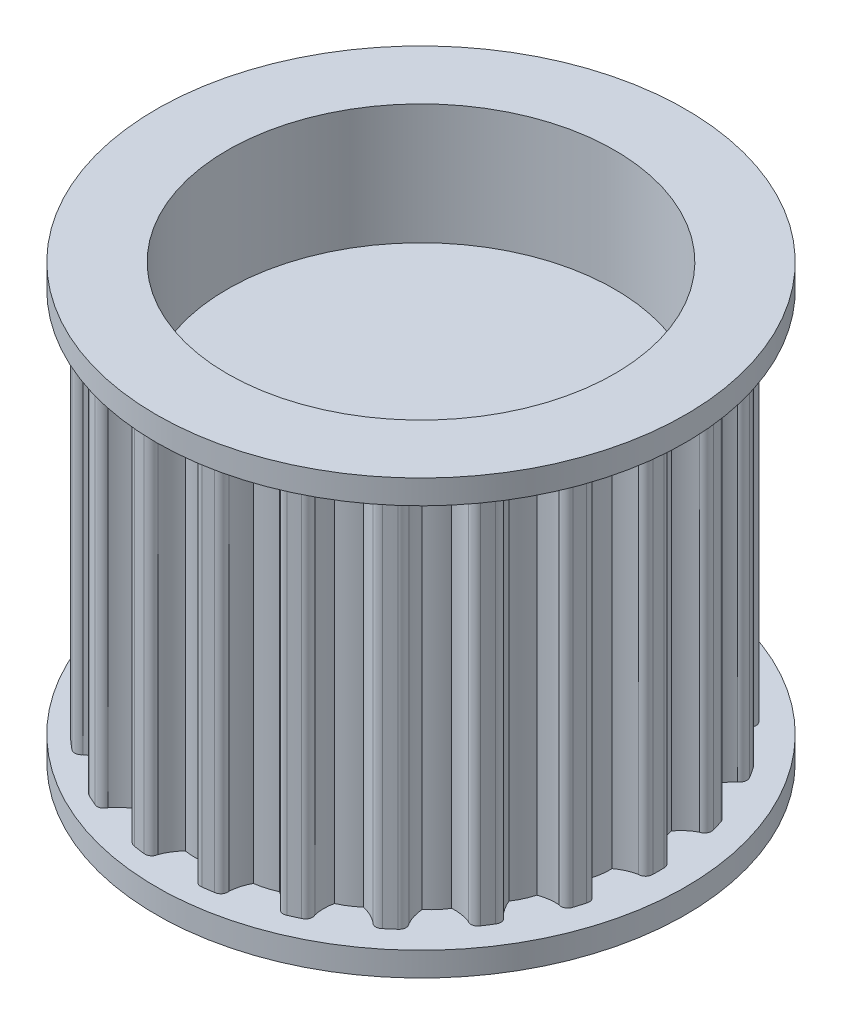
SolidWorks part; units mm, degrees
ref_plane "Front Plane" through (0, 0, 0) normal (0, 0, 1) x (1, 0, 0)
ref_plane "Top Plane" through (0, 0, 0) normal (0, 1, 0) x (1, 0, 0)
ref_plane "Right Plane" through (0, 0, 0) normal (1, 0, 0) x (0, 0, -1)
sketch "Sketch1" plane through (0, 0, 0) normal (0, 1, 0) x (1, 0, 0)
  arc A0 (-3.8587, 9.1521) -> (-4.2814, 9.2843) centre (-4.1212, 9.0547) ccw
  arc A1 (-4.2551, 9.3025) -> (-4.2814, 9.2843) centre (-2.0409, 6.0726) ccw
  arc A2 (-4.2551, 9.3025) -> (-4.6705, 9.1128) centre (-0.2578, 0) ccw
  arc A3 (-4.6394, 9.1208) -> (-4.6705, 9.1128) centre (-3.6795, 5.3243) ccw
  arc A4 (-4.6394, 9.1208) -> (-4.8163, 8.7148) centre (-4.5708, 8.8494) ccw
  arc A5 (-4.7705, 8.2917) -> (-4.8163, 8.7148) centre (-6.7455, 8.2917) ccw
  arc A6 (-4.8114, 7.8919) -> (-4.7705, 8.2917) centre (-6.7455, 8.2917) ccw
  arc A7 (-4.8114, 7.8919) -> (-5.5448, 7.4205) centre (-3.6795, 5.3243) ccw
  arc A8 (-6.2913, 7.7669) -> (-5.5448, 7.4205) centre (-5.1051, 9.3459) ccw
  arc A9 (-6.2913, 7.7669) -> (-6.7341, 7.7746) centre (-6.5157, 7.5994) ccw
  arc A10 (-6.714, 7.7995) -> (-6.7341, 7.7746) centre (-3.6795, 5.3243) ccw
  arc A11 (-6.714, 7.7995) -> (-7.0591, 7.5005) centre (-0.2578, 0) ccw
  arc A12 (-7.0316, 7.5169) -> (-7.0591, 7.5005) centre (-5.0409, 4.1446) ccw
  arc A13 (-7.0316, 7.5169) -> (-7.0869, 7.0775) centre (-6.8893, 7.2758) ccw
  arc A14 (-6.8503, 6.2893) -> (-7.0869, 7.0775) centre (-8.8187, 6.128) ccw
  arc A15 (-6.8503, 6.2893) -> (-7.4213, 5.6304) centre (-5.0409, 4.1446) ccw
  arc A16 (-8.2351, 5.7524) -> (-7.4213, 5.6304) centre (-7.5418, 7.6017) ccw
  arc A17 (-8.2351, 5.7524) -> (-8.6622, 5.6351) centre (-8.4032, 5.5285) ccw
  arc A18 (-8.6499, 5.6647) -> (-8.6622, 5.6351) centre (-5.0409, 4.1446) ccw
  arc A19 (-8.6499, 5.6647) -> (-8.8968, 5.2805) centre (-0.2578, 0) ccw
  arc A20 (-8.875, 5.304) -> (-8.8968, 5.2805) centre (-6.0148, 2.6292) ccw
  arc A21 (-8.875, 5.304) -> (-8.8043, 4.8668) centre (-8.6705, 5.1127) ccw
  arc A22 (-8.3552, 4.1772) -> (-8.8043, 4.8668) centre (-10.1984, 3.4679) ccw
  arc A23 (-8.3552, 4.1772) -> (-8.7174, 3.3841) centre (-6.0148, 2.6292) ccw
  arc A24 (-9.5326, 3.2719) -> (-8.7174, 3.3841) centre (-9.3883, 5.2417) ccw
  arc A25 (-9.5326, 3.2719) -> (-9.9093, 3.039) centre (-9.6309, 3.0097) ccw
  arc A26 (-9.9058, 3.0709) -> (-9.9093, 3.039) centre (-6.0148, 2.6292) ccw
  arc A27 (-9.9058, 3.0709) -> (-10.0345, 2.6327) centre (-0.2578, 0) ccw
  arc A28 (-10.0202, 2.6614) -> (-10.0345, 2.6327) centre (-6.5224, 0.9007) ccw
  arc A29 (-10.0202, 2.6614) -> (-9.8292, 2.2618) centre (-9.7701, 2.5355) ccw
  arc A30 (-9.204, 1.7267) -> (-9.8292, 2.2618) centre (-10.7728, 0.5268) ccw
  arc A31 (-9.204, 1.7267) -> (-9.3281, 0.8637) centre (-6.5224, 0.9007) ccw
  arc A32 (-10.0787, 0.5264) -> (-9.3281, 0.8637) centre (-10.4952, 2.457) ccw
  arc A33 (-10.0787, 0.5264) -> (-10.3746, 0.1968) centre (-10.0991, 0.2471) ccw
  arc A34 (-10.3802, 0.2283) -> (-10.3746, 0.1968) centre (-6.5224, 0.9007) ccw
  arc A35 (-10.3802, 0.2283) -> (-10.3828, 0) centre (-0.2578, 0) ccw
  arc A36 (-10.3828, 0) -> (-10.3802, -0.2283) centre (-0.2578, 0) ccw
  arc A37 (-10.3746, -0.1968) -> (-10.3802, -0.2283) centre (-6.5224, -0.9007) ccw
  arc A38 (-10.3746, -0.1968) -> (-10.0787, -0.5264) centre (-10.0991, -0.2471) ccw
  arc A39 (-9.3281, -0.8637) -> (-10.0787, -0.5264) centre (-10.4952, -2.457) ccw
  arc A40 (-9.3281, -0.8637) -> (-9.204, -1.7267) centre (-6.5224, -0.9007) ccw
  arc A41 (-9.8292, -2.2618) -> (-9.204, -1.7267) centre (-10.7728, -0.5268) ccw
  arc A42 (-9.8292, -2.2618) -> (-10.0202, -2.6614) centre (-9.7701, -2.5355) ccw
  arc A43 (-10.0345, -2.6327) -> (-10.0202, -2.6614) centre (-6.5224, -0.9007) ccw
  arc A44 (-10.0345, -2.6327) -> (-9.9058, -3.0709) centre (-0.2578, 0) ccw
  arc A45 (-9.9093, -3.039) -> (-9.9058, -3.0709) centre (-6.0148, -2.6292) ccw
  arc A46 (-9.9093, -3.039) -> (-9.5326, -3.2719) centre (-9.6309, -3.0097) ccw
  arc A47 (-8.7174, -3.3841) -> (-9.5326, -3.2719) centre (-9.3883, -5.2417) ccw
  arc A48 (-8.7174, -3.3841) -> (-8.3552, -4.1772) centre (-6.0148, -2.6292) ccw
  arc A49 (-8.8043, -4.8668) -> (-8.3552, -4.1772) centre (-10.1984, -3.4679) ccw
  arc A50 (-8.8043, -4.8668) -> (-8.875, -5.304) centre (-8.6705, -5.1127) ccw
  arc A51 (-8.8968, -5.2805) -> (-8.875, -5.304) centre (-6.0148, -2.6292) ccw
  arc A52 (-8.8968, -5.2805) -> (-8.6499, -5.6647) centre (-0.2578, 0) ccw
  arc A53 (-8.6622, -5.6351) -> (-8.6499, -5.6647) centre (-5.0409, -4.1446) ccw
  arc A54 (-8.6622, -5.6351) -> (-8.2351, -5.7524) centre (-8.4032, -5.5285) ccw
  arc A55 (-7.4213, -5.6304) -> (-8.2351, -5.7524) centre (-7.5418, -7.6017) ccw
  arc A56 (-7.4213, -5.6304) -> (-6.8503, -6.2893) centre (-5.0409, -4.1446) ccw
  arc A57 (-7.0869, -7.0775) -> (-6.8503, -6.2893) centre (-8.8187, -6.128) ccw
  arc A58 (-7.0869, -7.0775) -> (-7.0316, -7.5169) centre (-6.8893, -7.2758) ccw
  arc A59 (-7.0591, -7.5005) -> (-7.0316, -7.5169) centre (-5.0409, -4.1446) ccw
  arc A60 (-7.0591, -7.5005) -> (-6.714, -7.7995) centre (-0.2578, 0) ccw
  arc A61 (-6.7341, -7.7746) -> (-6.714, -7.7995) centre (-3.6795, -5.3243) ccw
  arc A62 (-6.7341, -7.7746) -> (-6.2913, -7.7669) centre (-6.5157, -7.5994) ccw
  arc A63 (-5.5448, -7.4205) -> (-6.2913, -7.7669) centre (-5.105, -9.3459) ccw
  arc A64 (-5.5448, -7.4205) -> (-4.8114, -7.8919) centre (-3.6795, -5.3243) ccw
  arc A65 (-4.7705, -8.2917) -> (-4.8114, -7.8919) centre (-6.7455, -8.2917) ccw
  arc A66 (-4.8163, -8.7148) -> (-4.7705, -8.2917) centre (-6.7455, -8.2917) ccw
  arc A67 (-4.8163, -8.7148) -> (-4.6394, -9.1208) centre (-4.5708, -8.8494) ccw
  arc A68 (-4.6705, -9.1128) -> (-4.6394, -9.1208) centre (-3.6795, -5.3243) ccw
  arc A69 (-4.6705, -9.1128) -> (-4.2551, -9.3025) centre (-0.2578, 0) ccw
  arc A70 (-4.2814, -9.2843) -> (-4.2551, -9.3025) centre (-2.0409, -6.0726) ccw
  arc A71 (-4.2814, -9.2843) -> (-3.8587, -9.1521) centre (-4.1212, -9.0547) ccw
  arc A72 (-3.2401, -8.6095) -> (-3.8587, -9.1521) centre (-2.2757, -10.333) ccw
  arc A73 (-3.2401, -8.6095) -> (-2.4035, -8.8551) centre (-2.0409, -6.0726) ccw
  arc A74 (-2.1765, -9.6461) -> (-2.4035, -8.8551) centre (-4.1467, -9.7836) ccw
  arc A75 (-2.1765, -9.6461) -> (-1.8923, -9.9858) centre (-1.903, -9.706) ccw
  arc A76 (-1.9244, -9.9869) -> (-1.8923, -9.9858) centre (-2.0409, -6.0726) ccw
  arc A77 (-1.9244, -9.9869) -> (-1.4723, -10.0519) centre (-0.2578, 0) ccw
  arc A78 (-1.5028, -10.0418) -> (-1.4723, -10.0519) centre (-0.2578, -6.329) ccw
  arc A79 (-1.5028, -10.0418) -> (-1.1344, -9.7959) centre (-1.4137, -9.7764) ccw
  arc A80 (-0.6937, -9.1009) -> (-1.1344, -9.7959) centre (0.7172, -10.4829) ccw
  arc A81 (-0.6937, -9.1009) -> (0.1782, -9.1009) centre (-0.2578, -6.329) ccw
  arc A82 (0.6189, -9.7959) -> (0.1782, -9.1009) centre (-1.2328, -10.4829) ccw
  arc A83 (0.6189, -9.7959) -> (0.9872, -10.0418) centre (0.8982, -9.7764) ccw
  arc A84 (0.9568, -10.0519) -> (0.9872, -10.0418) centre (-0.2578, -6.329) ccw
  arc A85 (0.9568, -10.0519) -> (1.4088, -9.9869) centre (-0.2578, 0) ccw
  arc A86 (1.3768, -9.9858) -> (1.4088, -9.9869) centre (1.5253, -6.0726) ccw
  arc A87 (1.3768, -9.9858) -> (1.6674, -9.706) centre (1.3874, -9.706) ccw
  arc A88 (1.6674, -9.706) -> (1.6609, -9.6461) centre (1.3874, -9.706) ccw
  arc A89 (1.888, -8.8551) -> (1.6609, -9.6461) centre (3.6311, -9.7836) ccw
  arc A90 (1.888, -8.8551) -> (2.7245, -8.6095) centre (1.5253, -6.0726) ccw
  arc A91 (3.3432, -9.1521) -> (2.7245, -8.6095) centre (1.7601, -10.333) ccw
  arc A92 (3.3432, -9.1521) -> (3.7659, -9.2843) centre (3.6057, -9.0547) ccw
  arc A93 (3.7395, -9.3025) -> (3.7659, -9.2843) centre (1.5253, -6.0726) ccw
  arc A94 (3.7395, -9.3025) -> (4.1549, -9.1128) centre (-0.2578, 0) ccw
  arc A95 (4.1239, -9.1208) -> (4.1549, -9.1128) centre (3.1639, -5.3243) ccw
  arc A96 (4.1239, -9.1208) -> (4.3353, -8.8494) centre (4.0553, -8.8494) ccw
  arc A97 (4.3353, -8.8494) -> (4.3008, -8.7148) centre (4.0553, -8.8494) ccw
  arc A98 (4.2958, -7.8919) -> (4.3008, -8.7148) centre (6.2299, -8.2917) ccw
  arc A99 (4.2958, -7.8919) -> (5.0293, -7.4205) centre (3.1639, -5.3243) ccw
  arc A100 (5.7758, -7.7669) -> (5.0293, -7.4205) centre (4.5895, -9.3459) ccw
  arc A101 (5.7758, -7.7669) -> (6.2186, -7.7746) centre (6.0002, -7.5994) ccw
  arc A102 (6.1984, -7.7995) -> (6.2186, -7.7746) centre (3.1639, -5.3243) ccw
  arc A103 (6.1984, -7.7995) -> (6.5436, -7.5005) centre (-0.2578, 0) ccw
  arc A104 (6.516, -7.5169) -> (6.5436, -7.5005) centre (4.5254, -4.1446) ccw
  arc A105 (6.516, -7.5169) -> (6.6537, -7.2758) centre (6.3737, -7.2758) ccw
  arc A106 (6.6537, -7.2758) -> (6.5714, -7.0775) centre (6.3737, -7.2758) ccw
  arc A107 (6.3348, -6.2893) -> (6.5714, -7.0775) centre (8.3032, -6.128) ccw
  arc A108 (6.3348, -6.2893) -> (6.9057, -5.6304) centre (4.5254, -4.1446) ccw
  arc A109 (7.7195, -5.7524) -> (6.9057, -5.6304) centre (7.0262, -7.6017) ccw
  arc A110 (7.7195, -5.7524) -> (8.1466, -5.6351) centre (7.8877, -5.5285) ccw
  arc A111 (8.1343, -5.6647) -> (8.1466, -5.6351) centre (4.5254, -4.1446) ccw
  arc A112 (8.1343, -5.6647) -> (8.3812, -5.2805) centre (-0.2578, 0) ccw
  arc A113 (8.3594, -5.304) -> (8.3812, -5.2805) centre (5.4993, -2.6292) ccw
  arc A114 (8.3594, -5.304) -> (8.4349, -5.1127) centre (8.1549, -5.1127) ccw
  arc A115 (8.4349, -5.1127) -> (8.2887, -4.8668) centre (8.1549, -5.1127) ccw
  arc A116 (7.8396, -4.1772) -> (8.2887, -4.8668) centre (9.6829, -3.4679) ccw
  arc A117 (7.8396, -4.1772) -> (8.2018, -3.3841) centre (5.4993, -2.6292) ccw
  arc A118 (9.017, -3.2719) -> (8.2018, -3.3841) centre (8.8728, -5.2417) ccw
  arc A119 (9.017, -3.2719) -> (9.3938, -3.039) centre (9.1153, -3.0097) ccw
  arc A120 (9.3903, -3.0709) -> (9.3938, -3.039) centre (5.4993, -2.6292) ccw
  arc A121 (9.3903, -3.0709) -> (9.5189, -2.6327) centre (-0.2578, 0) ccw
  arc A122 (9.5047, -2.6614) -> (9.5189, -2.6327) centre (6.0068, -0.9007) ccw
  arc A123 (9.5047, -2.6614) -> (9.5346, -2.5355) centre (9.2546, -2.5355) ccw
  arc A124 (9.5346, -2.5355) -> (9.3136, -2.2618) centre (9.2546, -2.5355) ccw
  arc A125 (8.6885, -1.7267) -> (9.3136, -2.2618) centre (10.2572, -0.5268) ccw
  arc A126 (8.6885, -1.7267) -> (8.8128, -0.9007) centre (6.0068, -0.9007) ccw
  arc A127 (8.8128, -0.9007) -> (8.8126, -0.8637) centre (6.0068, -0.9007) ccw
  arc A128 (9.5632, -0.5264) -> (8.8126, -0.8637) centre (9.9797, -2.457) ccw
  arc A129 (9.5632, -0.5264) -> (9.8636, -0.2471) centre (9.5836, -0.2471) ccw
  arc A130 (9.8636, -0.2471) -> (9.859, -0.1968) centre (9.5836, -0.2471) ccw
  arc A131 (9.8646, -0.2283) -> (9.859, -0.1968) centre (6.0068, -0.9007) ccw
  arc A132 (9.8646, -0.2283) -> (9.8646, 0.2283) centre (-0.2578, 0) ccw
  arc A133 (9.859, 0.1968) -> (9.8646, 0.2283) centre (6.0068, 0.9007) ccw
  arc A134 (9.859, 0.1968) -> (9.8636, 0.2471) centre (9.5836, 0.2471) ccw
  arc A135 (9.8636, 0.2471) -> (9.5632, 0.5264) centre (9.5836, 0.2471) ccw
  arc A136 (8.8126, 0.8637) -> (9.5632, 0.5264) centre (9.9797, 2.457) ccw
  arc A137 (8.8126, 0.8637) -> (8.8128, 0.9007) centre (6.0068, 0.9007) ccw
  arc A138 (8.8128, 0.9007) -> (8.6885, 1.7267) centre (6.0068, 0.9007) ccw
  arc A139 (9.3136, 2.2618) -> (8.6885, 1.7267) centre (10.2572, 0.5268) ccw
  arc A140 (9.3136, 2.2618) -> (9.5346, 2.5355) centre (9.2546, 2.5355) ccw
  arc A141 (9.5346, 2.5355) -> (9.5047, 2.6614) centre (9.2546, 2.5355) ccw
  arc A142 (9.5189, 2.6327) -> (9.5047, 2.6614) centre (6.0068, 0.9007) ccw
  arc A143 (9.5189, 2.6327) -> (9.3903, 3.0709) centre (-0.2578, 0) ccw
  arc A144 (9.3938, 3.039) -> (9.3903, 3.0709) centre (5.4993, 2.6292) ccw
  arc A145 (9.3938, 3.039) -> (9.017, 3.2719) centre (9.1153, 3.0097) ccw
  arc A146 (8.2018, 3.3841) -> (9.017, 3.2719) centre (8.8728, 5.2417) ccw
  arc A147 (8.2018, 3.3841) -> (7.8396, 4.1772) centre (5.4993, 2.6292) ccw
  arc A148 (8.2887, 4.8668) -> (7.8396, 4.1772) centre (9.6829, 3.4679) ccw
  arc A149 (8.2887, 4.8668) -> (8.4349, 5.1127) centre (8.1549, 5.1127) ccw
  arc A150 (8.4349, 5.1127) -> (8.3594, 5.304) centre (8.1549, 5.1127) ccw
  arc A151 (8.3812, 5.2805) -> (8.3594, 5.304) centre (5.4993, 2.6292) ccw
  arc A152 (8.3812, 5.2805) -> (8.1343, 5.6647) centre (-0.2578, 0) ccw
  arc A153 (8.1466, 5.6351) -> (8.1343, 5.6647) centre (4.5254, 4.1446) ccw
  arc A154 (8.1466, 5.6351) -> (7.7195, 5.7524) centre (7.8877, 5.5285) ccw
  arc A155 (6.9057, 5.6304) -> (7.7195, 5.7524) centre (7.0262, 7.6017) ccw
  arc A156 (6.9057, 5.6304) -> (6.3348, 6.2893) centre (4.5254, 4.1446) ccw
  arc A157 (6.5714, 7.0775) -> (6.3348, 6.2893) centre (8.3032, 6.128) ccw
  arc A158 (6.5714, 7.0775) -> (6.6537, 7.2758) centre (6.3737, 7.2758) ccw
  arc A159 (6.6537, 7.2758) -> (6.516, 7.5169) centre (6.3737, 7.2758) ccw
  arc A160 (6.5436, 7.5005) -> (6.516, 7.5169) centre (4.5254, 4.1446) ccw
  arc A161 (6.5436, 7.5005) -> (6.1984, 7.7995) centre (-0.2578, 0) ccw
  arc A162 (6.2186, 7.7746) -> (6.1984, 7.7995) centre (3.1639, 5.3243) ccw
  arc A163 (6.2186, 7.7746) -> (5.7758, 7.7669) centre (6.0002, 7.5994) ccw
  arc A164 (5.0293, 7.4205) -> (5.7758, 7.7669) centre (4.5895, 9.3459) ccw
  arc A165 (5.0293, 7.4205) -> (4.2958, 7.8919) centre (3.1639, 5.3243) ccw
  arc A166 (4.3008, 8.7148) -> (4.2958, 7.8919) centre (6.2299, 8.2917) ccw
  arc A167 (4.3008, 8.7148) -> (4.3353, 8.8494) centre (4.0553, 8.8494) ccw
  arc A168 (4.3353, 8.8494) -> (4.1239, 9.1208) centre (4.0553, 8.8494) ccw
  arc A169 (4.1549, 9.1128) -> (4.1239, 9.1208) centre (3.1639, 5.3243) ccw
  arc A170 (4.1549, 9.1128) -> (3.7395, 9.3025) centre (-0.2578, 0) ccw
  arc A171 (3.7659, 9.2843) -> (3.7395, 9.3025) centre (1.5253, 6.0726) ccw
  arc A172 (3.7659, 9.2843) -> (3.3432, 9.1521) centre (3.6057, 9.0547) ccw
  arc A173 (2.7245, 8.6095) -> (3.3432, 9.1521) centre (1.7601, 10.333) ccw
  arc A174 (2.7245, 8.6095) -> (1.888, 8.8551) centre (1.5253, 6.0726) ccw
  arc A175 (1.6609, 9.6461) -> (1.888, 8.8551) centre (3.6311, 9.7836) ccw
  arc A176 (1.6609, 9.6461) -> (1.6674, 9.706) centre (1.3874, 9.706) ccw
  arc A177 (1.6674, 9.706) -> (1.3768, 9.9858) centre (1.3874, 9.706) ccw
  arc A178 (1.4088, 9.9869) -> (1.3768, 9.9858) centre (1.5253, 6.0726) ccw
  arc A179 (1.4088, 9.9869) -> (0.9568, 10.0519) centre (-0.2578, 0) ccw
  arc A180 (0.9872, 10.0418) -> (0.9568, 10.0519) centre (-0.2578, 6.329) ccw
  arc A181 (0.9872, 10.0418) -> (0.6189, 9.7959) centre (0.8982, 9.7764) ccw
  arc A182 (0.1782, 9.1009) -> (0.6189, 9.7959) centre (-1.2328, 10.4829) ccw
  arc A183 (0.1782, 9.1009) -> (-0.6937, 9.1009) centre (-0.2578, 6.329) ccw
  arc A184 (-1.1344, 9.7959) -> (-0.6937, 9.1009) centre (0.7172, 10.4829) ccw
  arc A185 (-1.1344, 9.7959) -> (-1.5028, 10.0418) centre (-1.4137, 9.7764) ccw
  arc A186 (-1.4723, 10.0519) -> (-1.5028, 10.0418) centre (-0.2578, 6.329) ccw
  arc A187 (-1.4723, 10.0519) -> (-1.9244, 9.9869) centre (-0.2578, 0) ccw
  arc A188 (-1.8923, 9.9858) -> (-1.9244, 9.9869) centre (-2.0409, 6.0726) ccw
  arc A189 (-1.8923, 9.9858) -> (-2.1765, 9.6461) centre (-1.903, 9.706) ccw
  arc A190 (-2.4035, 8.8551) -> (-2.1765, 9.6461) centre (-4.1467, 9.7836) ccw
  arc A191 (-2.4035, 8.8551) -> (-3.2401, 8.6095) centre (-2.0409, 6.0726) ccw
  arc A192 (-3.8587, 9.1521) -> (-3.2401, 8.6095) centre (-2.2757, 10.333) ccw
extrude "Boss-Extrude1" add sketch "Sketch1" along normal blind 16
sketch "Sketch2" plane through (0, 16, 0) normal (0, 1, 0) x (1, 0, 0)
  circle A0 centre (0, 0) radius 11
extrude "Boss-Extrude2" add sketch "Sketch2" along normal blind 1
sketch "Sketch3" plane through (0, 0, 0) normal (0, -1, 0) x (1, 0, 0)
  circle A0 centre (0, 0) radius 11 construction
  circle A1 centre (0, 0) radius 11
extrude "Boss-Extrude3" add sketch "Sketch3" along normal blind 1
sketch "Sketch4" plane through (0, -1, 0) normal (0, -1, 0) x (1, 0, 0)
  circle A0 centre (0, 0) radius 8.05
extrude "Cut-Extrude1" cut sketch "Sketch4" against normal blind 5
sketch "Sketch5" plane through (0, 17, 0) normal (0, 1, 0) x (1, 0, 0)
  circle A1 centre (0, 0) radius 8.05
  circle A2 centre (0, 0) radius 8.05
  dimension "D1" = 0
extrude "Cut-Extrude2" cut sketch "Sketch5" against normal blind 5
